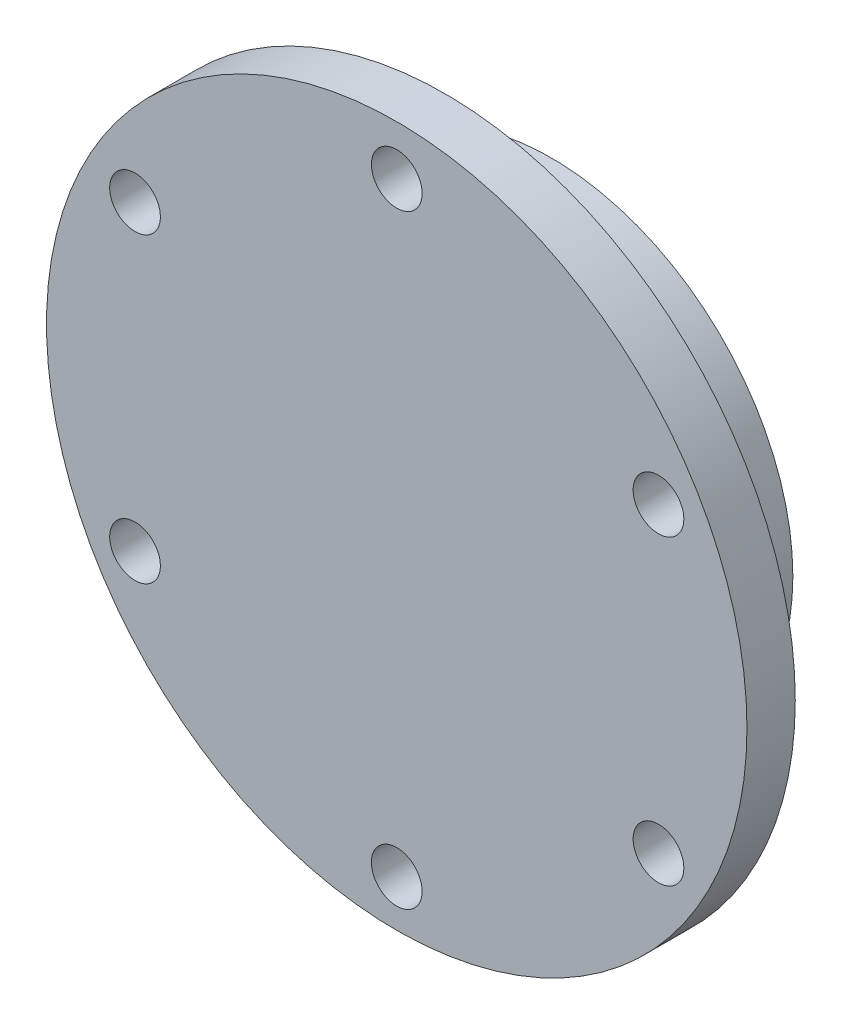
SolidWorks part; units mm, degrees
ref_plane "Alzado" through (0, 0, 0) normal (0, 0, 1) x (1, 0, 0)
ref_plane "Planta" through (0, 0, 0) normal (0, 1, 0) x (1, 0, 0)
ref_plane "Vista lateral" through (0, 0, 0) normal (1, 0, 0) x (0, 0, -1)
sketch "Croquis1" plane through (0, 0, 0) normal (0, 0, 1) x (1, 0, 0)
  circle A0 centre (0, 0) radius 72.5
  dimension "D1" = 145
extrude "Saliente-Extruir1" add sketch "Croquis1" along normal blind 10
sketch "Croquis10" plane through (0, 0, 0) normal (0, 0, -1) x (-1, 0, 0)
  line L0 (0, 0) -> (0, 89.2963)
hole_wizard "Taladro roscado M12x1.51" positions "Croquis3D5" profile "Croquis12" tap size "M12x1.5" standard "Ansi Metric"
sketch3d "Croquis3D5"
  line L0 (0, 0, 0) -> (0, 89.2963, 0) construction
  point P0 (0, 62.2336, 0)
sketch "Croquis12" plane through (0, 62.2336, 0) normal (1, 0, 0) x (0, 1, 0)
  line L0 (0, 0) -> (0, 34.6545)
  line L1 (0, 34.6545) -> (5.25, 31.5)
  line L2 (5.25, 31.5) -> (5.25, 0)
  line L5 (5.25, 0) -> (0, 0)
  line L10 (0, 34.6545) -> (-5.25, 31.5) construction
  line L11 (0, -6.35) -> (0, 107.95) construction
  dimension "Diámetro de perforador para roscar" = 10.5
  dimension "Profundidad de perforador para roscar" = 31.5
  dimension "Ángulo de perforador" = 118
pattern_circular "MatrizC3" count 6 over 360 about axis through (0, -0.3281, 0) along (0, 0, 1) of "Taladro roscado M12x1.51"
sketch "Croquis13" plane through (0, 0, 0) normal (0, 0, -1) x (-1, 0, 0)
  circle A0 centre (0, 0) radius 50
  circle A1 centre (54.18, 30.9528) radius 5.25 construction
  circle A2 centre (0, 62.2336) radius 5.25 construction
  dimension "D1" = 100
extrude "Saliente-Extruir2" add sketch "Croquis13" along normal blind 22
